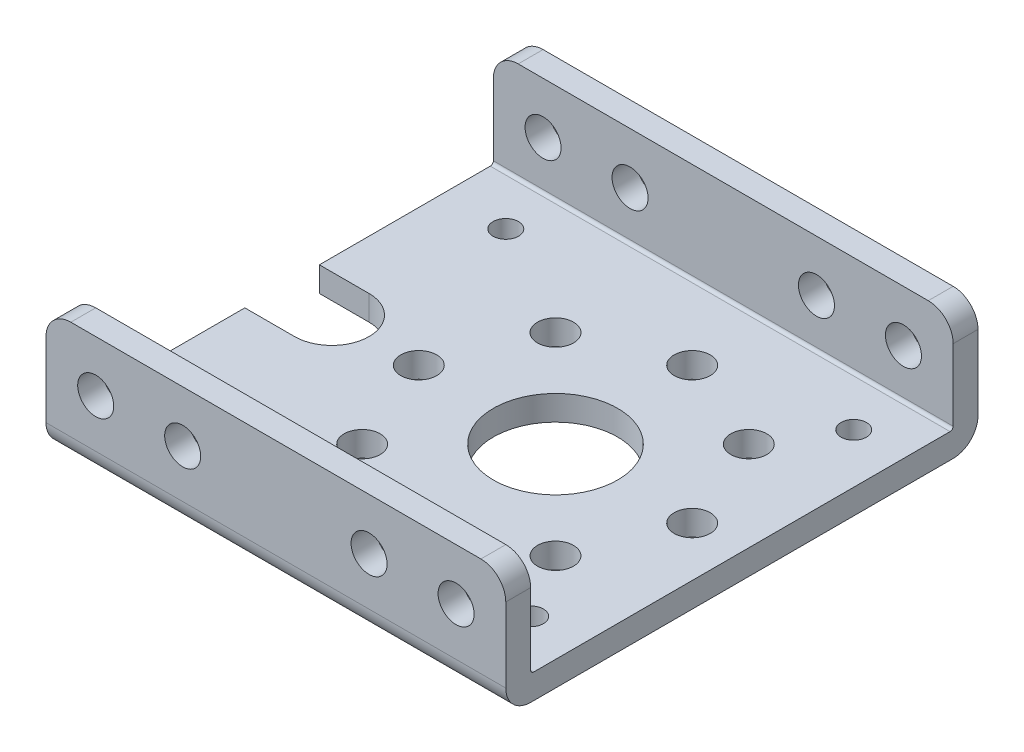
SolidWorks part; units mm, degrees
material "1060 Alloy"
ref_plane "Front Plane" through (0, 0, 0) normal (0, 0, 1) x (1, 0, 0)
ref_plane "Top Plane" through (0, 0, 0) normal (0, 1, 0) x (1, 0, 0)
ref_plane "Right Plane" through (0, 0, 0) normal (1, 0, 0) x (0, 0, -1)
sketch "Sketch1" plane through (0, 0, 0) normal (0, 1, 0) x (1, 0, 0)
  line L0 (-14.5, 3) -> (-18.5, 3)
  line L1 (-18.5, 19) -> (18.5, 19)
  line L2 (-18.5, 19) -> (-18.5, 3)
  line L3 (-18.5, -19) -> (18.5, -19)
  line L4 (18.5, 19) -> (18.5, -19)
  line L5 (-18.5, 19) -> (18.5, -19) construction
  line L6 (-18.5, -19) -> (18.5, 19) construction
  line L7 (-14.5, -3) -> (-18.5, -3)
  line L8 (-18.5, -3) -> (-18.5, -19)
  arc A0 (-14.5, -3) -> (-14.5, 3) centre (-14.5, 0) ccw
  point P0 (0, 0)
  dimension "D3" = 6
  dimension "D1" = 37
  dimension "D2" = 38
  dimension "D4" = 4
extrude "Boss-Extrude1" add sketch "Sketch1" along normal blind 2
sketch "Sketch2" plane through (0, 2, 0) normal (0, 1, 0) x (1, 0, 0)
  line L0 (18.5, -19) -> (18.5, 19) construction
  line L1 (-18.5, 19) -> (18.5, 19)
  line L2 (-18.5, 19) -> (-18.5, 17)
  line L3 (-18.5, 17) -> (18.5, 17)
  line L4 (18.5, 19) -> (18.5, 17)
  line L6 (-18.5, -19) -> (18.5, -19)
  line L7 (-18.5, -19) -> (-18.5, -16.9983)
  line L8 (-18.5, -16.9983) -> (18.5, -16.9983)
  line L9 (18.5, -19) -> (18.5, -16.9983)
  dimension "D1" = 2
  dimension "D2" = 2.0017
extrude "Boss-Extrude2" add sketch "Sketch2" along normal blind 8
fillet "Fillet1" radius 2 6 edges at (0, 0, -19) (0, 0, 19) (-18.5, 10, -18) (-18.5, 10, 17.9991) (18.5, 10, -18) (18.5, 10, 17.9991)
fillet "Fillet2" radius 0.25 2 edges at (0, 2, 16.9983) (0, 2, -17)
hole_wizard "Tap Drill for M2.5 Tap1" positions "Sketch3" profile "Sketch4" hole size "M2.5" standard "ISO" end condition up to next
sketch "Sketch3" plane through (0, 2, 0) normal (0, 1, 0) x (1, 0, 0)
  line L0 (-18.5, 16.75) -> (-18.5, 3) construction
  line L1 (-18.5, 17) -> (18.5, 17) construction
  line L2 (-18.5, -3) -> (-18.5, -16.7483) construction
  line L3 (-16.5, -19) -> (16.5, -19) construction
  line L4 (16.5, 19) -> (-16.5, 19) construction
  line L5 (18.5, -16.7483) -> (18.5, 16.75) construction
  point P0 (-13.5, 13)
  point P2 (14.5, 13)
  point P4 (14.5, -13)
  point P6 (-13.5, -13)
  dimension "D1" = 5
  dimension "D2" = 4
  dimension "D3" = 5
  dimension "D4" = 6
  dimension "D5" = 6
  dimension "D6" = 6
  dimension "D7" = 4
  dimension "D8" = 4
sketch "Sketch4" plane through (-13.5, 2, -13) normal (1, 0, 0) x (0, 0, 1)
  line L0 (0, 0) -> (0, 2)
  line L1 (0, 2) -> (1.025, 2)
  line L2 (1.025, 2) -> (1.025, 0)
  line L5 (1.025, 0) -> (0, 0)
  line L11 (0, -6.35) -> (0, 107.95) construction
  dimension "Thru Hole Dia." = 2.05
  dimension "Thru Hole Depth" = 2
sketch "Sketch5" plane through (0, 2, 0) normal (0, 1, 0) x (1, 0, 0)
  line L0 (18.5, -16.7483) -> (18.5, 16.75) construction
  circle A0 centre (3.5, 0) radius 5
  dimension "D1" = 10
  dimension "D2" = 15
extrude "Cut-Extrude1" cut sketch "Sketch5" against normal through all
sketch "Sketch8" plane through (0, 2, 0) normal (0, 1, 0) x (1, 0, 0)
  circle A0 centre (3.5, 0) radius 11 construction
  dimension "D1" = 22
hole_wizard "M2.5 Clearance Hole1" positions "Sketch11" profile "Sketch12" hole size "M2.5" standard "ISO" end condition up to next
sketch "Sketch11" plane through (0, 2, 0) normal (0, 1, 0) x (1, 0, 0)
  circle A0 centre (3.5, 0) radius 11 construction
  point P0 (3.5, 11)
sketch "Sketch12" plane through (3.5, 2, -11) normal (1, 0, 0) x (0, 0, 1)
  line L0 (0, 0) -> (0, 2.001)
  line L1 (0, 2.001) -> (1.45, 2.001)
  line L2 (1.45, 2.001) -> (1.45, 0)
  line L5 (1.45, 0) -> (0, 0)
  line L11 (0, -6.35) -> (0, 107.95) construction
  dimension "Thru Hole Dia." = 2.9
  dimension "Thru Hole Depth" = 2.001
pattern_circular "CirPattern1" count 8 over 360 about axis through (3.5, 0, 0) along (0, 1, 0) of "M2.5 Clearance Hole1"
hole_wizard "M2.5 Clearance Hole2" positions "Sketch13" profile "Sketch14" hole size "M2.5" standard "ISO" end condition through all
sketch "Sketch13" plane through (0, 0, 19) normal (0, 0, 1) x (1, 0, 0)
  line L0 (-18.5, 8) -> (-18.5, 2) construction
  line L1 (18.5, 8) -> (18.5, 2.25) construction
  point P0 (-14.5, 5.8701)
  point P2 (-7.5, 5.8701)
  point P4 (7.5, 5.8701)
  point P6 (14.5, 5.8701)
  dimension "D1" = 4
  dimension "D2" = 4
  dimension "D3" = 7
  dimension "D4" = 7
  dimension "D5" = 22
sketch "Sketch14" plane through (-14.5, 5.8701, 19) normal (1, 0, 0) x (0, -1, 0)
  line L0 (0, 0) -> (0, 38)
  line L1 (0, 38) -> (1.45, 38)
  line L2 (1.45, 38) -> (1.45, 0)
  line L5 (1.45, 0) -> (0, 0)
  line L11 (0, -6.35) -> (0, 107.95) construction
  dimension "Thru Hole Dia." = 2.9
  dimension "Thru Hole Depth" = 38
